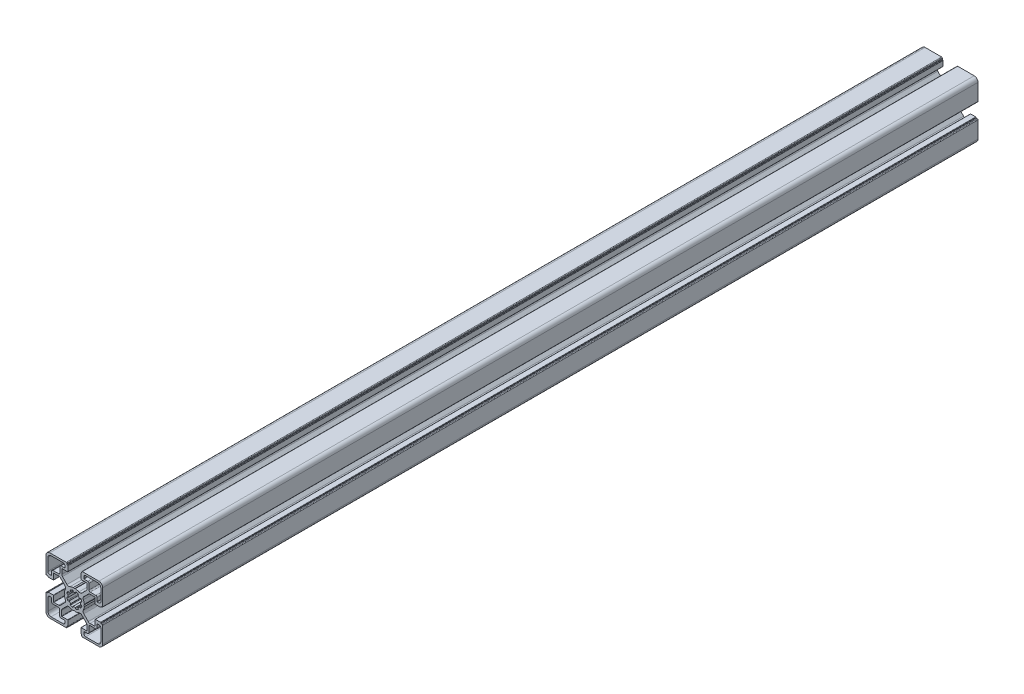
SolidWorks part; units mm, degrees
material "3.1355 (EN-AW 2024)"
ref_plane "Спереди" through (0, 0, 0) normal (0, 0, 1) x (1, 0, 0)
ref_plane "Сверху" through (0, 0, 0) normal (0, 1, 0) x (1, 0, 0)
ref_plane "Справа" through (0, 0, 0) normal (1, 0, 0) x (0, 0, -1)
sketch "Model" plane through (0, 0, 0) normal (0, 0, 1) x (1, 0, 0)
  line L0 (-18.1765, 7.5) -> (-19.4765, 7.5)
  line L1 (-20.9765, 9) -> (-20.9765, 18.5)
  line L2 (-18.4765, 21) -> (-8.9767, 21)
  line L3 (-7.4767, 19.5) -> (-7.4767, 18.2)
  line L4 (-7.6767, 18) -> (-10.471, 18)
  line L5 (-11.471, 17) -> (-11.471, 12.6054)
  line L6 (-12.471, 11.6054) -> (-16.9765, 11.6054)
  line L7 (-17.9765, 10.6054) -> (-17.9765, 7.7)
  line L8 (3.2148, 4.5626) -> (2.8875, 4.0985)
  line L9 (4.1132, 2.8765) -> (4.5903, 3.2082)
  line L10 (5.5132, 0.9862) -> (4.944, 0.8878)
  line L11 (4.944, -0.8878) -> (5.5132, -0.9862)
  line L12 (4.5903, -3.2082) -> (4.1132, -2.8765)
  line L13 (2.8875, -4.0985) -> (3.2148, -4.5626)
  line L14 (0.991, -5.4811) -> (0.8909, -4.9242)
  line L15 (-0.8439, -4.9242) -> (-0.944, -5.4811)
  line L16 (-3.1678, -4.5626) -> (-2.8405, -4.0985)
  line L17 (-4.0662, -2.8765) -> (-4.5433, -3.2082)
  line L18 (-5.4663, -0.9862) -> (-4.8971, -0.8878)
  line L19 (-4.8971, 0.8878) -> (-5.4663, 0.9862)
  line L20 (-4.5433, 3.2082) -> (-4.0662, 2.8765)
  line L21 (-2.8405, 4.0985) -> (-3.1678, 4.5626)
  line L22 (-0.944, 5.4811) -> (-0.8439, 4.9242)
  line L23 (0.8909, 4.9242) -> (0.991, 5.4811)
  line L24 (18.2235, -7.5) -> (19.5235, -7.5)
  line L25 (21.0235, -9) -> (21.0235, -18.5)
  line L26 (18.5235, -21) -> (9.0237, -21)
  line L27 (7.5237, -19.5) -> (7.5237, -18.2)
  line L28 (7.7237, -18) -> (10.518, -18)
  line L29 (11.518, -17) -> (11.518, -12.6054)
  line L30 (12.518, -11.6054) -> (17.0235, -11.6054)
  line L31 (18.0235, -10.6054) -> (18.0235, -7.7)
  line L32 (7.5235, 18.2) -> (7.5235, 19.5)
  line L33 (9.0235, 21) -> (18.5235, 21)
  line L34 (21.0235, 18.5) -> (21.0235, 9.0002)
  line L35 (19.5235, 7.5002) -> (18.2235, 7.5002)
  line L36 (18.0235, 7.7002) -> (18.0235, 10.4945)
  line L37 (17.0235, 11.4945) -> (12.6289, 11.4945)
  line L38 (11.6289, 12.4945) -> (11.6289, 17)
  line L39 (10.6289, 18) -> (7.7235, 18)
  line L40 (-7.4765, -18.2) -> (-7.4765, -19.5)
  line L41 (-8.9765, -21) -> (-18.4765, -21)
  line L42 (-20.9765, -18.5) -> (-20.9765, -9.0002)
  line L43 (-19.4765, -7.5002) -> (-18.1765, -7.5002)
  line L44 (-17.9765, -7.7002) -> (-17.9765, -10.4945)
  line L45 (-16.9765, -11.4945) -> (-12.5819, -11.4945)
  line L46 (-11.5819, -12.4945) -> (-11.5819, -17)
  line L47 (-10.5819, -18) -> (-7.6765, -18)
  line L48 (-7.5269, -5.8456) -> (-11.1063, -9.425)
  line L49 (-12.4813, -9.9945) -> (-16.2765, -9.9945)
  line L50 (-16.4765, -9.7945) -> (-16.4765, -5.35)
  line L51 (-16.6765, -5.15) -> (-20.6765, -5.15)
  line L52 (-20.9765, -5.45) -> (-20.9765, -5.5757)
  line L53 (-21.2765, -5.8757) -> (-21.9765, -5.8757)
  line L54 (-22.4765, -6.3757) -> (-22.4765, -19.5)
  line L55 (-19.4765, -22.5) -> (-6.3522, -22.5)
  line L56 (-5.8522, -22) -> (-5.8522, -21.3)
  line L57 (-5.5522, -21) -> (-5.4265, -21)
  line L58 (-5.1265, -20.7) -> (-5.1265, -16.7)
  line L59 (-5.3265, -16.5) -> (-9.8819, -16.5)
  line L60 (-10.0819, -16.3) -> (-10.0819, -12.4716)
  line L61 (-9.4961, -11.0574) -> (-5.9333, -7.4945)
  line L62 (-0.7736, -7.9602) -> (0.0235, -7.5)
  line L63 (0.0235, -7.5) -> (0.8206, -7.9602)
  line L64 (5.869, -7.5503) -> (9.4485, -11.1298)
  line L65 (10.018, -12.5048) -> (10.018, -16.3)
  line L66 (9.818, -16.5) -> (5.3735, -16.5)
  line L67 (5.1735, -16.7) -> (5.1735, -20.7)
  line L68 (5.4735, -21) -> (5.5992, -21)
  line L69 (5.8992, -21.3) -> (5.8992, -22)
  line L70 (6.3992, -22.5) -> (19.5235, -22.5)
  line L71 (22.5235, -19.5) -> (22.5235, -6.3757)
  line L72 (22.0235, -5.8757) -> (21.3235, -5.8757)
  line L73 (21.0235, -5.5757) -> (21.0235, -5.45)
  line L74 (20.7235, -5.15) -> (16.7235, -5.15)
  line L75 (16.5235, -5.35) -> (16.5235, -9.9054)
  line L76 (16.3235, -10.1054) -> (12.4951, -10.1054)
  line L77 (11.0808, -9.5196) -> (7.518, -5.9567)
  line L78 (7.9837, -0.7971) -> (7.5235, 0)
  line L79 (7.5235, 0) -> (7.9837, 0.7971)
  line L80 (7.5738, 5.8456) -> (11.1533, 9.425)
  line L81 (12.5282, 9.9945) -> (16.3235, 9.9945)
  line L82 (16.5235, 9.7945) -> (16.5235, 5.35)
  line L83 (16.7235, 5.15) -> (20.7235, 5.15)
  line L84 (21.0235, 5.45) -> (21.0235, 5.5757)
  line L85 (21.3235, 5.8757) -> (22.0235, 5.8757)
  line L86 (22.5235, 6.3757) -> (22.5235, 19.5)
  line L87 (19.5235, 22.5) -> (6.3992, 22.5)
  line L88 (5.8992, 22) -> (5.8992, 21.3)
  line L89 (5.5992, 21) -> (5.4735, 21)
  line L90 (5.1735, 20.7) -> (5.1735, 16.7)
  line L91 (5.3735, 16.5) -> (9.9289, 16.5)
  line L92 (10.1289, 16.3) -> (10.1289, 12.4716)
  line L93 (9.5431, 11.0574) -> (5.9802, 7.4945)
  line L94 (0.8206, 7.9602) -> (0.0235, 7.5)
  line L95 (0.0235, 7.5) -> (-0.7736, 7.9602)
  line L96 (-5.8221, 7.5503) -> (-9.4015, 11.1298)
  line L97 (-9.971, 12.5048) -> (-9.971, 16.3)
  line L98 (-9.771, 16.5) -> (-5.3265, 16.5)
  line L99 (-5.1265, 16.7) -> (-5.1265, 20.7)
  line L100 (-5.4265, 21) -> (-5.5523, 21)
  line L101 (-5.8523, 21.3) -> (-5.8523, 22)
  line L102 (-6.3523, 22.5) -> (-19.4765, 22.5)
  line L103 (-22.4765, 19.5) -> (-22.4765, 6.3757)
  line L104 (-21.9765, 5.8757) -> (-21.2765, 5.8757)
  line L105 (-20.9765, 5.5757) -> (-20.9765, 5.45)
  line L106 (-20.6765, 5.15) -> (-16.6765, 5.15)
  line L107 (-16.4765, 5.35) -> (-16.4765, 9.9054)
  line L108 (-16.2765, 10.1054) -> (-12.4481, 10.1054)
  line L109 (-11.0339, 9.5196) -> (-7.471, 5.9567)
  line L110 (-7.9367, 0.7971) -> (-7.4765, 0)
  line L111 (-7.4765, 0) -> (-7.9367, -0.7971)
  arc A0 (-18.1765, 7.5) -> (-17.9765, 7.7) centre (-18.1765, 7.7) ccw
  arc A1 (-20.9765, 9) -> (-19.4765, 7.5) centre (-19.4765, 9) ccw
  arc A2 (-18.4765, 21) -> (-20.9765, 18.5) centre (-18.4765, 18.5) ccw
  arc A3 (-7.4767, 19.5) -> (-8.9767, 21) centre (-8.9767, 19.5) ccw
  arc A4 (-7.6767, 18) -> (-7.4767, 18.2) centre (-7.6767, 18.2) ccw
  arc A5 (-10.471, 18) -> (-11.471, 17) centre (-10.471, 17) ccw
  arc A6 (-12.471, 11.6054) -> (-11.471, 12.6054) centre (-12.471, 12.6054) ccw
  arc A7 (-16.9765, 11.6054) -> (-17.9765, 10.6054) centre (-16.9765, 10.6054) ccw
  arc A8 (3.2148, 4.5626) -> (3.0679, 5.2994) centre (2.8177, 4.8665) ccw
  arc A9 (4.1132, 2.8765) -> (2.8875, 4.0985) centre (0.0235, 0) ccw
  arc A10 (5.326, 3.0565) -> (4.5903, 3.2082) centre (4.8915, 2.8091) ccw
  arc A11 (5.9303, 1.6112) -> (5.326, 3.0565) centre (0.047, 0) ccw
  arc A12 (5.5132, 0.9862) -> (5.9303, 1.6112) centre (5.4473, 1.4819) ccw
  arc A13 (4.944, -0.8878) -> (4.944, 0.8878) centre (0.0235, 0) ccw
  arc A14 (5.9303, -1.6112) -> (5.5132, -0.9862) centre (5.4473, -1.4819) ccw
  arc A15 (5.326, -3.0565) -> (5.9303, -1.6112) centre (0.047, 0) ccw
  arc A16 (4.5903, -3.2082) -> (5.326, -3.0565) centre (4.8915, -2.8091) ccw
  arc A17 (2.8875, -4.0985) -> (4.1132, -2.8765) centre (0.0235, 0) ccw
  arc A18 (3.0679, -5.2994) -> (3.2148, -4.5626) centre (2.8177, -4.8665) ccw
  arc A19 (1.6185, -5.8941) -> (3.0679, -5.2994) centre (0.047, 0) ccw
  arc A20 (0.991, -5.4811) -> (1.6185, -5.8941) centre (1.4862, -5.4119) ccw
  arc A21 (-0.8439, -4.9242) -> (0.8909, -4.9242) centre (0.0235, 0) ccw
  arc A22 (-1.5716, -5.8941) -> (-0.944, -5.4811) centre (-1.4392, -5.4119) ccw
  arc A23 (-3.0209, -5.2994) -> (-1.5716, -5.8941) centre (0, 0) ccw
  arc A24 (-3.1678, -4.5626) -> (-3.0209, -5.2994) centre (-2.7708, -4.8665) ccw
  arc A25 (-4.0662, -2.8765) -> (-2.8405, -4.0985) centre (0.0235, 0) ccw
  arc A26 (-5.279, -3.0565) -> (-4.5433, -3.2082) centre (-4.8445, -2.8091) ccw
  arc A27 (-5.8834, -1.6112) -> (-5.279, -3.0565) centre (0, 0) ccw
  arc A28 (-5.4663, -0.9862) -> (-5.8834, -1.6112) centre (-5.4004, -1.4819) ccw
  arc A29 (-4.8971, 0.8878) -> (-4.8971, -0.8878) centre (0.0235, 0) ccw
  arc A30 (-5.8834, 1.6112) -> (-5.4663, 0.9862) centre (-5.4004, 1.4819) ccw
  arc A31 (-5.279, 3.0565) -> (-5.8834, 1.6112) centre (0, 0) ccw
  arc A32 (-4.5433, 3.2082) -> (-5.279, 3.0565) centre (-4.8445, 2.8091) ccw
  arc A33 (-2.8405, 4.0985) -> (-4.0662, 2.8765) centre (0.0235, 0) ccw
  arc A34 (-3.0209, 5.2994) -> (-3.1678, 4.5626) centre (-2.7708, 4.8665) ccw
  arc A35 (-1.5716, 5.8941) -> (-3.0209, 5.2994) centre (0, 0) ccw
  arc A36 (-0.944, 5.4811) -> (-1.5716, 5.8941) centre (-1.4392, 5.4119) ccw
  arc A37 (0.8909, 4.9242) -> (-0.8439, 4.9242) centre (0.0235, 0) ccw
  arc A38 (1.6185, 5.8941) -> (0.991, 5.4811) centre (1.4862, 5.4119) ccw
  arc A39 (3.0679, 5.2994) -> (1.6185, 5.8941) centre (0.047, 0) ccw
  arc A40 (18.2235, -7.5) -> (18.0235, -7.7) centre (18.2235, -7.7) ccw
  arc A41 (21.0235, -9) -> (19.5235, -7.5) centre (19.5235, -9) ccw
  arc A42 (18.5235, -21) -> (21.0235, -18.5) centre (18.5235, -18.5) ccw
  arc A43 (7.5237, -19.5) -> (9.0237, -21) centre (9.0237, -19.5) ccw
  arc A44 (7.7237, -18) -> (7.5237, -18.2) centre (7.7237, -18.2) ccw
  arc A45 (10.518, -18) -> (11.518, -17) centre (10.518, -17) ccw
  arc A46 (12.518, -11.6054) -> (11.518, -12.6054) centre (12.518, -12.6054) ccw
  arc A47 (17.0235, -11.6054) -> (18.0235, -10.6054) centre (17.0235, -10.6054) ccw
  arc A48 (7.5235, 18.2) -> (7.7235, 18) centre (7.7235, 18.2) ccw
  arc A49 (9.0235, 21) -> (7.5235, 19.5) centre (9.0235, 19.5) ccw
  arc A50 (21.0235, 18.5) -> (18.5235, 21) centre (18.5235, 18.5) ccw
  arc A51 (19.5235, 7.5002) -> (21.0235, 9.0002) centre (19.5235, 9.0002) ccw
  arc A52 (18.0235, 7.7002) -> (18.2235, 7.5002) centre (18.2235, 7.7002) ccw
  arc A53 (18.0235, 10.4945) -> (17.0235, 11.4945) centre (17.0235, 10.4945) ccw
  arc A54 (11.6289, 12.4945) -> (12.6289, 11.4945) centre (12.6289, 12.4945) ccw
  arc A55 (11.6289, 17) -> (10.6289, 18) centre (10.6289, 17) ccw
  arc A56 (-7.4765, -18.2) -> (-7.6765, -18) centre (-7.6765, -18.2) ccw
  arc A57 (-8.9765, -21) -> (-7.4765, -19.5) centre (-8.9765, -19.5) ccw
  arc A58 (-20.9765, -18.5) -> (-18.4765, -21) centre (-18.4765, -18.5) ccw
  arc A59 (-19.4765, -7.5002) -> (-20.9765, -9.0002) centre (-19.4765, -9.0002) ccw
  arc A60 (-17.9765, -7.7002) -> (-18.1765, -7.5002) centre (-18.1765, -7.7002) ccw
  arc A61 (-17.9765, -10.4945) -> (-16.9765, -11.4945) centre (-16.9765, -10.4945) ccw
  arc A62 (-11.5819, -12.4945) -> (-12.5819, -11.4945) centre (-12.5819, -12.4945) ccw
  arc A63 (-11.5819, -17) -> (-10.5819, -18) centre (-10.5819, -17) ccw
  arc A64 (-7.5269, -5.8456) -> (-7.1482, -3.5451) centre (-8.9411, -4.4313) ccw
  arc A65 (-12.4813, -9.9945) -> (-11.1063, -9.425) centre (-12.4813, -8.05) ccw
  arc A66 (-16.4765, -9.7945) -> (-16.2765, -9.9945) centre (-16.2765, -9.7945) ccw
  arc A67 (-16.4765, -5.35) -> (-16.6765, -5.15) centre (-16.6765, -5.35) ccw
  arc A68 (-20.6765, -5.15) -> (-20.9765, -5.45) centre (-20.6765, -5.45) ccw
  arc A69 (-21.2765, -5.8757) -> (-20.9765, -5.5757) centre (-21.2765, -5.5757) ccw
  arc A70 (-21.9765, -5.8757) -> (-22.4765, -6.3757) centre (-21.9765, -6.3757) ccw
  arc A71 (-22.4765, -19.5) -> (-19.4765, -22.5) centre (-19.4765, -19.5) ccw
  arc A72 (-6.3522, -22.5) -> (-5.8522, -22) centre (-6.3522, -22) ccw
  arc A73 (-5.5522, -21) -> (-5.8522, -21.3) centre (-5.5522, -21.3) ccw
  arc A74 (-5.4265, -21) -> (-5.1265, -20.7) centre (-5.4265, -20.7) ccw
  arc A75 (-5.1265, -16.7) -> (-5.3265, -16.5) centre (-5.3265, -16.7) ccw
  arc A76 (-10.0819, -16.3) -> (-9.8819, -16.5) centre (-9.8819, -16.3) ccw
  arc A77 (-9.4961, -11.0574) -> (-10.0819, -12.4716) centre (-8.0819, -12.4716) ccw
  arc A78 (-3.6105, -7.127) -> (-5.9333, -7.4945) centre (-4.5191, -8.9087) ccw
  arc A79 (-3.6105, -7.127) -> (-0.7736, -7.9602) centre (0.0235, 0) ccw
  arc A80 (0.8206, -7.9602) -> (3.5686, -7.1716) centre (0.0235, 0) ccw
  arc A81 (5.869, -7.5503) -> (3.5686, -7.1716) centre (4.4548, -8.9646) ccw
  arc A82 (10.018, -12.5048) -> (9.4485, -11.1298) centre (8.0735, -12.5048) ccw
  arc A83 (9.818, -16.5) -> (10.018, -16.3) centre (9.818, -16.3) ccw
  arc A84 (5.3735, -16.5) -> (5.1735, -16.7) centre (5.3735, -16.7) ccw
  arc A85 (5.1735, -20.7) -> (5.4735, -21) centre (5.4735, -20.7) ccw
  arc A86 (5.8992, -21.3) -> (5.5992, -21) centre (5.5992, -21.3) ccw
  arc A87 (5.8992, -22) -> (6.3992, -22.5) centre (6.3992, -22) ccw
  arc A88 (19.5235, -22.5) -> (22.5235, -19.5) centre (19.5235, -19.5) ccw
  arc A89 (22.5235, -6.3757) -> (22.0235, -5.8757) centre (22.0235, -6.3757) ccw
  arc A90 (21.0235, -5.5757) -> (21.3235, -5.8757) centre (21.3235, -5.5757) ccw
  arc A91 (21.0235, -5.45) -> (20.7235, -5.15) centre (20.7235, -5.45) ccw
  arc A92 (16.7235, -5.15) -> (16.5235, -5.35) centre (16.7235, -5.35) ccw
  arc A93 (16.3235, -10.1054) -> (16.5235, -9.9054) centre (16.3235, -9.9054) ccw
  arc A94 (11.0808, -9.5196) -> (12.4951, -10.1054) centre (12.4951, -8.1054) ccw
  arc A95 (7.1505, -3.634) -> (7.518, -5.9567) centre (8.9322, -4.5425) ccw
  arc A96 (7.1505, -3.634) -> (7.9837, -0.7971) centre (0.0235, 0) ccw
  arc A97 (7.9837, 0.7971) -> (7.1951, 3.5451) centre (0.0235, 0) ccw
  arc A98 (7.5738, 5.8456) -> (7.1951, 3.5451) centre (8.988, 4.4313) ccw
  arc A99 (12.5282, 9.9945) -> (11.1533, 9.425) centre (12.5282, 8.05) ccw
  arc A100 (16.5235, 9.7945) -> (16.3235, 9.9945) centre (16.3235, 9.7945) ccw
  arc A101 (16.5235, 5.35) -> (16.7235, 5.15) centre (16.7235, 5.35) ccw
  arc A102 (20.7235, 5.15) -> (21.0235, 5.45) centre (20.7235, 5.45) ccw
  arc A103 (21.3235, 5.8757) -> (21.0235, 5.5757) centre (21.3235, 5.5757) ccw
  arc A104 (22.0235, 5.8757) -> (22.5235, 6.3757) centre (22.0235, 6.3757) ccw
  arc A105 (22.5235, 19.5) -> (19.5235, 22.5) centre (19.5235, 19.5) ccw
  arc A106 (6.3992, 22.5) -> (5.8992, 22) centre (6.3992, 22) ccw
  arc A107 (5.5992, 21) -> (5.8992, 21.3) centre (5.5992, 21.3) ccw
  arc A108 (5.4735, 21) -> (5.1735, 20.7) centre (5.4735, 20.7) ccw
  arc A109 (5.1735, 16.7) -> (5.3735, 16.5) centre (5.3735, 16.7) ccw
  arc A110 (10.1289, 16.3) -> (9.9289, 16.5) centre (9.9289, 16.3) ccw
  arc A111 (9.5431, 11.0574) -> (10.1289, 12.4716) centre (8.1289, 12.4716) ccw
  arc A112 (3.6575, 7.127) -> (5.9802, 7.4945) centre (4.566, 8.9087) ccw
  arc A113 (3.6575, 7.127) -> (0.8206, 7.9602) centre (0.0235, 0) ccw
  arc A114 (-0.7736, 7.9602) -> (-3.5216, 7.1716) centre (0.0235, 0) ccw
  arc A115 (-5.8221, 7.5503) -> (-3.5216, 7.1716) centre (-4.4079, 8.9646) ccw
  arc A116 (-9.971, 12.5048) -> (-9.4015, 11.1298) centre (-8.0265, 12.5048) ccw
  arc A117 (-9.771, 16.5) -> (-9.971, 16.3) centre (-9.771, 16.3) ccw
  arc A118 (-5.3265, 16.5) -> (-5.1265, 16.7) centre (-5.3265, 16.7) ccw
  arc A119 (-5.1265, 20.7) -> (-5.4265, 21) centre (-5.4265, 20.7) ccw
  arc A120 (-5.8523, 21.3) -> (-5.5523, 21) centre (-5.5523, 21.3) ccw
  arc A121 (-5.8523, 22) -> (-6.3523, 22.5) centre (-6.3523, 22) ccw
  arc A122 (-19.4765, 22.5) -> (-22.4765, 19.5) centre (-19.4765, 19.5) ccw
  arc A123 (-22.4765, 6.3757) -> (-21.9765, 5.8757) centre (-21.9765, 6.3757) ccw
  arc A124 (-20.9765, 5.5757) -> (-21.2765, 5.8757) centre (-21.2765, 5.5757) ccw
  arc A125 (-20.9765, 5.45) -> (-20.6765, 5.15) centre (-20.6765, 5.45) ccw
  arc A126 (-16.6765, 5.15) -> (-16.4765, 5.35) centre (-16.6765, 5.35) ccw
  arc A127 (-16.2765, 10.1054) -> (-16.4765, 9.9054) centre (-16.2765, 9.9054) ccw
  arc A128 (-11.0339, 9.5196) -> (-12.4481, 10.1054) centre (-12.4481, 8.1054) ccw
  arc A129 (-7.1035, 3.634) -> (-7.471, 5.9567) centre (-8.8853, 4.5425) ccw
  arc A130 (-7.1035, 3.634) -> (-7.9367, 0.7971) centre (0.0235, 0) ccw
  arc A131 (-7.9367, -0.7971) -> (-7.1482, -3.5451) centre (0.0235, 0) ccw
extrude "Бобышка-Вытянуть1" add sketch "Model" against normal blind 695
